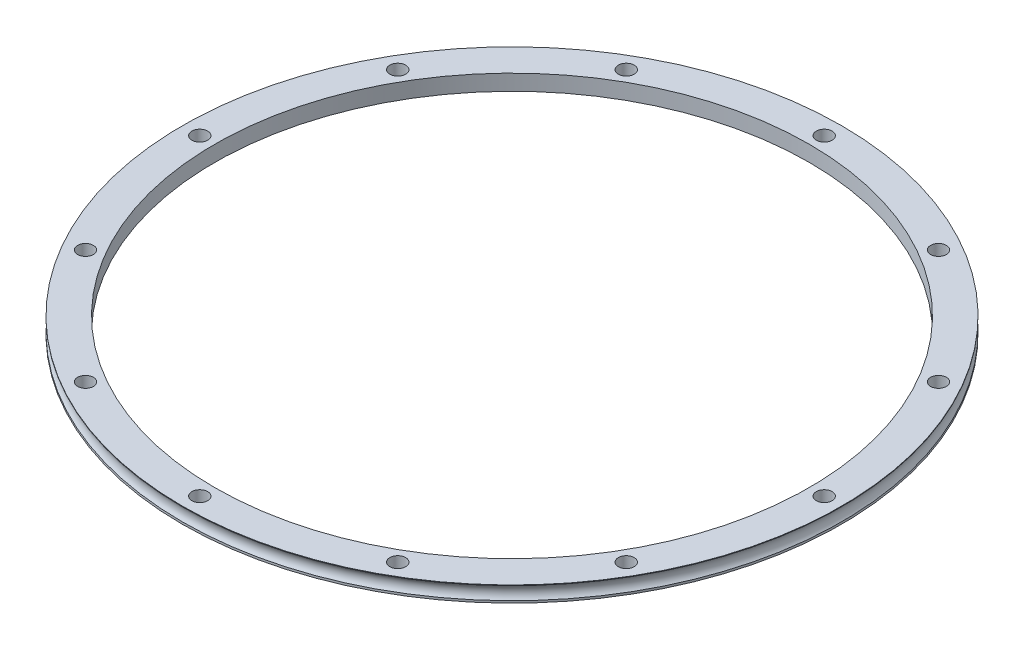
SolidWorks part; units mm, degrees
material "AISI 4340 Steel, normalized"
ref_plane "Front Plane" through (0, 0, 0) normal (0, 0, 1) x (1, 0, 0)
ref_plane "Top Plane" through (0, 0, 0) normal (0, 1, 0) x (1, 0, 0)
ref_plane "Right Plane" through (0, 0, 0) normal (1, 0, 0) x (0, 0, -1)
sketch "Sketch1" plane through (0, 0, 0) normal (0, 0, 1) x (1, 0, 0)
  line L1 (-60, 6.785) -> (-60, 9.965) construction
  line L2 (-60, 6.785) -> (-66.5, 6.785) construction
  line L3 (-66.5, 6.785) -> (-66.5, 7.218) construction
  line L4 (-66.5, 9.852) -> (-66.5, 9.965)
  line L5 (-60, 6.785) -> (-60, 9.965)
  line L6 (-60, 6.785) -> (-66.5, 6.785)
  line L7 (-66.5, 6.785) -> (-66.5, 7.218)
  line L8 (-60, 9.965) -> (-66.5, 9.965)
  line L10 (0, -200069.0475) -> (0, 200086.9028) construction
  line L11 (0, -200069.0475) -> (0, 200086.9028) construction
  arc A0 (-66.5, 7.218) -> (-66.5, 9.852) centre (-67.9844, 8.535) ccw construction
  arc A1 (-66.5, 7.218) -> (-66.5, 9.852) centre (-67.9844, 8.535) ccw
revolve "Revolve1" add sketch "Sketch1" angle 360 about L11
ref_plane "Midplane" through (0, 8.375, 0) normal (0, 1, 0) x (1, 0, 0)
split "Split1" [suppressed] bodies to split 101
sketch "Sketch3" plane through (0, 9.965, 0) normal (0, 1, 0) x (1, 0, 0)
  circle A1 centre (0, 63) radius 1.6
  circle A2 centre (0, 63) radius 1.6
  dimension "D1" = 0
extrude "Cut-Extrude1" cut sketch "Sketch3" against normal through all
pattern_circular "CirPattern1" count 12 over 360 about axis through (0, 0, 0) along (0, 1, 0) of "Cut-Extrude1"
